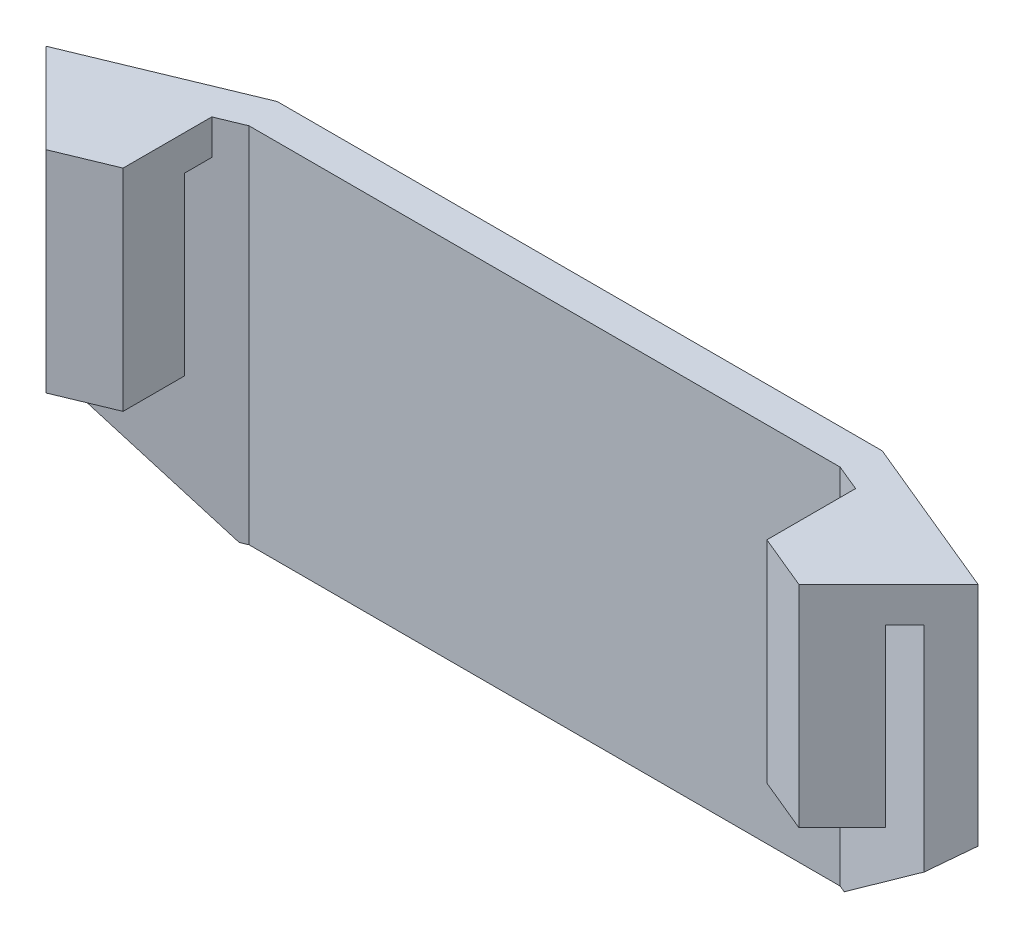
SolidWorks part; units mm, degrees
ref_plane "Front Plane" through (0, 0, 0) normal (0, 0, 1) x (1, 0, 0)
ref_plane "Top Plane" through (0, 0, 0) normal (0, 1, 0) x (1, 0, 0)
ref_plane "Right Plane" through (0, 0, 0) normal (1, 0, 0) x (0, 0, -1)
sketch "Sketch2" plane through (0, 0, 0) normal (0, 1, 0) x (1, 0, 0)
  line L0 (-27.25, -8.4052) -> (-27.25, -0.8284)
  line L1 (-27.25, -0.8284) -> (-25.25, 0)
  line L2 (-25.25, 0) -> (25.25, 0)
  line L3 (25.25, 0) -> (27.25, -0.8284)
  line L4 (27.25, -0.8284) -> (27.25, -8.4052)
  line L5 (27.25, -8.4052) -> (36.1559, -12.0941)
  line L6 (36.1559, -12.0941) -> (41.5135, -6.7365)
  line L7 (41.5135, -3.4894) -> (25.8467, 3)
  line L8 (25.8467, 3) -> (-25.8467, 3)
  line L9 (-27.25, -8.4052) -> (-36.1559, -12.0941)
  line L10 (-36.1559, -12.0941) -> (-41.5135, -6.7365)
  line L11 (-41.5135, -3.4894) -> (-25.8467, 3)
  line L12 (-41.5135, -3.4894) -> (-41.5135, -6.7365)
  line L13 (41.5135, -3.4894) -> (41.5135, -6.7365)
  point P12 (0, 0)
  dimension "D1" = 3
  dimension "D2" = 3
  dimension "D3" = 3
  dimension "D4" = 202.5
  dimension "D5" = 202.5
  dimension "D6" = 7
  dimension "D7" = 9.6397
  dimension "D8" = 67.5
  dimension "D9" = 67.5
  dimension "D10" = 2.1648
  dimension "D11" = 27.25
extrude "Boss-Extrude1" add sketch "Sketch2" along normal blind 3
sketch "Sketch3" plane through (0, 0, 0) normal (0, -1, 0) x (1, 0, 0)
  line L0 (-41.5135, 6.7365) -> (-25.25, 0)
  line L1 (-25.25, 0) -> (25.25, 0)
  line L2 (25.25, 0) -> (41.5135, 6.7365)
  line L3 (41.5135, 6.7365) -> (41.5135, 3.4894)
  line L4 (41.5135, 3.4894) -> (25.8467, -3)
  line L5 (25.8467, -3) -> (-25.8467, -3)
  line L6 (-25.8467, -3) -> (-41.5135, 3.4894)
  line L7 (-41.5135, 3.4894) -> (-41.5135, 6.7365)
extrude "Boss-Extrude2" add sketch "Sketch3" along normal blind 28
sketch "Sketch4" plane through (-4.8458, 0, -11.6989) normal (-0.3827, 0, -0.9239) x (-0.9239, 0, 0.3827)
  line L10 (40.9314, -14) -> (22.7312, -28)
  line L11 (40.9314, -28) -> (40.9314, 0) construction
  line L12 (22.7312, -28) -> (40.9314, -28)
  line L13 (40.9314, -28) -> (40.9314, -14)
extrude "Cut-Extrude1" cut sketch "Sketch4" along direction (0, 0, -1) on the side against the normal blind 30
sketch "Sketch5" plane through (4.8458, 0, -11.6989) normal (0.3827, 0, -0.9239) x (-0.9239, 0, -0.3827)
  line L5 (-40.9314, -14) -> (-22.7312, -28)
  line L6 (-40.9314, -28) -> (-40.9314, 0) construction
  line L7 (-22.7312, -28) -> (-40.9314, -28)
  line L8 (-40.9314, -28) -> (-40.9314, -14)
extrude "Cut-Extrude2" cut sketch "Sketch5" along direction (0, 0, 1) on the side against the normal blind 30
sketch "Sketch6" plane through (0, 3, 0) normal (0, 1, 0) x (1, 0, 0)
  line L1 (-39.8096, -2.7836) -> (-32.1559, -10.4373)
  line L5 (39.8096, -2.7836) -> (32.1559, -10.4373)
  line L6 (27.25, -8.4052) -> (36.1559, -12.0941) construction
  line L7 (32.1559, -10.4373) -> (36.1559, -12.0941)
  line L8 (36.1559, -12.0941) -> (41.5135, -6.7365)
  line L9 (41.5135, -6.7365) -> (41.5135, -3.4894)
  line L11 (-36.1559, -12.0941) -> (-27.25, -8.4052) construction
  line L15 (-41.5135, -6.7365) -> (-41.5135, -3.4894)
  line L16 (-32.1559, -10.4373) -> (-36.1559, -12.0941)
  line L17 (-36.1559, -12.0941) -> (-41.5135, -6.7365)
  line L18 (41.5135, -3.4894) -> (25.8467, 3) construction
  line L19 (41.5135, -3.4894) -> (39.8096, -2.7836)
  line L20 (-41.5135, -3.4894) -> (-39.8096, -2.7836)
  line L21 (-25.8467, 3) -> (-41.5135, -3.4894) construction
  dimension "D1" = 4
  dimension "D2" = 4
extrude "Cut-Extrude3" cut sketch "Sketch6" against normal up to surface (31 mm away) up to face at (0, -28, -0.9176)
sketch "Sketch7" plane through (0, 3, 0) normal (0, 1, 0) x (1, 0, 0)
  line L0 (-25.25, 0) -> (-27.5, -0.932)
  line L1 (-27.5, -0.932) -> (-27.5, -8.5087)
  line L2 (-32.1559, -10.4373) -> (-27.25, -8.4052) construction
  line L3 (-27.5, -8.5087) -> (27.5, -8.5087)
  line L4 (27.25, -8.4052) -> (32.1559, -10.4373) construction
  line L5 (27.5, -8.5087) -> (27.5, -0.932)
  line L6 (-25.25, 0) -> (25.25, 0)
  line L7 (25.25, 0) -> (27.5, -0.932)
  dimension "D1" = 55
  dimension "D2" = 157.5
  dimension "D3" = 157.5
extrude "Cut-Extrude4" cut sketch "Sketch7" against normal up to surface (31 mm away) up to face at (0, -28, -0.9176)
sketch "Sketch8" plane through (0, 0, 0) normal (0, -1, 0) x (1, 0, 0)
  line L0 (-32.1559, 10.4373) -> (-27.5, 8.5087)
  line L1 (-27.5, 8.5087) -> (-27.5, 3.2591)
  line L2 (-27.5, 8.5087) -> (-27.5, 0.932) construction
  line L3 (-27.5, 3.2591) -> (-35.8679, 6.7252)
  line L4 (-37.5135, 5.0797) -> (-32.1559, 10.4373) construction
  line L5 (-35.8679, 6.7252) -> (-32.1559, 10.4373)
  line L6 (-27.5, 0.932) -> (-37.5135, 5.0797) construction
  line L7 (0, 0) -> (0, -3) construction
  line L8 (25.25, 0) -> (-25.25, 0) construction
  line L9 (-25.8467, -3) -> (25.8467, -3) construction
  line L10 (27.5, 3.2591) -> (35.8679, 6.7252)
  line L11 (27.5, 8.5087) -> (27.5, 3.2591)
  line L12 (32.1559, 10.4373) -> (27.5, 8.5087)
  line L13 (35.8679, 6.7252) -> (32.1559, 10.4373)
  dimension "D1" = 2.15
extrude "Boss-Extrude3" add sketch "Sketch8" along normal blind 15
